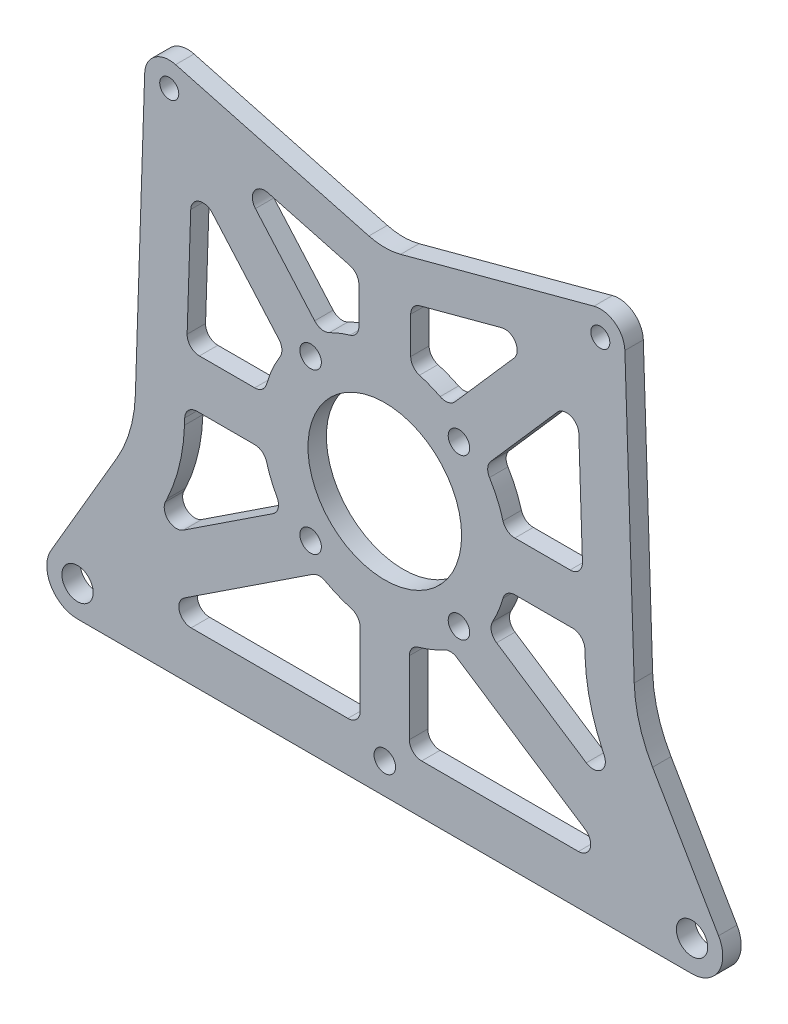
SolidWorks part; units mm, degrees
ref_plane "前视基准面" through (0, 0, 0) normal (0, 0, 1) x (1, 0, 0)
ref_plane "上视基准面" through (0, 0, 0) normal (0, 1, 0) x (1, 0, 0)
ref_plane "右视基准面" through (0, 0, 0) normal (1, 0, 0) x (0, 0, -1)
other "Configuration Table"
sketch "草图1" plane through (0, 0, 0) normal (0, 0, 1) x (1, 0, 0)
  line L0 (0, 0) -> (0, 112) construction
  line L1 (72.7192, 112) -> (-72.7192, 112) construction
  line L2 (-45, 15) -> (-95, 15) construction
  line L3 (-39.0719, 87.3817) -> (-40.5902, 41.2759)
  line L4 (-50, 5) -> (0, 5)
  line L5 (-54.3176, 12.5216) -> (-43.581, 30.9048)
  line L6 (-25, 5) -> (25, 5) construction
  line L7 (0, 5) -> (0, 96.5)
  line L8 (-34.0395, 91.1139) -> (0, 82)
  line L9 (-55, 10) -> (-55, 0)
  line L10 (-88.7574, 0) -> (88.7574, 0) construction
  line L11 (12.07, 35) -> (-12.07, 35) construction
  line L12 (12.07, 35) -> (12.07, 61) construction
  line L13 (12.07, 61) -> (-12.07, 61) construction
  line L14 (-12.07, 35) -> (-12.07, 61) construction
  line L15 (12.07, 35) -> (-12.07, 61) construction
  line L16 (12.07, 61) -> (-12.07, 35) construction
  line L17 (-55, 0) -> (0, 0)
  line L18 (0, 0) -> (0, 5)
  circle A0 centre (-35.074, 87.25) radius 1.55
  circle A4 centre (-50, 10) radius 2.55
  arc A5 (-45, 5) -> (-45, 15) centre (-45, 10) ccw construction
  circle A6 centre (-35.074, 87.25) radius 4
  circle A7 centre (-50, 10) radius 5
  circle A8 centre (-12.07, 61) radius 1.75
  circle A9 centre (12.07, 61) radius 1.75
  circle A10 centre (-12.07, 35) radius 1.75
  circle A11 centre (12.07, 35) radius 1.75
  arc A12 (-62.5783, 20) -> (-43.5752, 53.0852) centre (-62.5783, 42) ccw construction
  arc A13 (-62.5783, 20) -> (-40.5902, 41.2759) centre (-62.5783, 42) ccw
  point P32 (0, 48)
  dimension "D1" = 5
  dimension "D3" = 26
  dimension "D5" = 8
  dimension "D6" = 3.1
  dimension "D8" = 5.1
  dimension "D9" = 10
  dimension "D11" = 3.5
  dimension "D12" = 3.5
  dimension "D13" = 3.5
  dimension "D14" = 3.5
  dimension "D2" = 5
  dimension "D4" = 24.14
  dimension "D7" = 35
  dimension "D10" = 55
  dimension "D15" = 47
extrude "凸台-拉伸1" add sketch "草图1" along normal blind 3 contours A13 L5 A7 L4 L7 L8 A6 L3 A10 A8 | A6 A0 | A7 A4
mirror "镜向1" about plane through (0, 0, 3) normal (-1, 0, 0) of "凸台-拉伸1"
fillet "圆角1" radius 10 1 edges at (0, 82, 1.5)
sketch "草图2" plane through (0, 0, 3) normal (0, 0, 1) x (1, 0, 0)
  line L0 (25, 15) -> (-25, 15) construction
  circle A0 centre (0, 10) radius 1.75
  point P5 (0, 10)
  dimension "D1" = 5
  dimension "D3" = 3.5
  dimension "D2" = 10
extrude "切除-拉伸1" cut sketch "草图2" against normal blind 3
sketch "草图4" plane through (0, 0, 3) normal (0, 0, 1) x (1, 0, 0)
  line L0 (0, 61) -> (0, 35) construction
  line L1 (-12.07, 61) -> (12.07, 61)
  line L2 (-12.07, 61) -> (-12.07, 35)
  line L3 (-12.07, 35) -> (12.07, 35)
  line L4 (12.07, 61) -> (12.07, 35)
  line L5 (-12.07, 48) -> (12.07, 48) construction
  line L6 (12.07, 35) -> (50, 10) construction
  line L7 (35.074, 87.25) -> (12.07, 61) construction
  line L8 (-35.074, 87.25) -> (-12.07, 61) construction
  line L9 (-50, 10) -> (-12.07, 35) construction
  line L10 (0, 35) -> (0, 10) construction
  line L11 (0, 68) -> (0, 82.3522)
  line L12 (0, 28) -> (0, 10)
  line L13 (-32.5946, 41.0126) -> (-31.0762, 87.1183)
  line L14 (-39.0719, 87.3817) -> (-40.5902, 41.2759) construction
  line L15 (-39.0719, 87.3817) -> (-40.5902, 41.2759)
  line L16 (-31.4094, 76.9992) -> (-16.2336, 59.682)
  line L17 (-35.4302, 29.2337) -> (-45.4753, 7.8723)
  line L18 (-38.7284, 22.2199) -> (-16.5814, 36.8172)
  line L19 (-25.3928, 82.2718) -> (-10.217, 64.9546)
  line L20 (-25.3928, 82.2718) -> (-4.217, 76.6021)
  line L21 (-34.0395, 91.1139) -> (-2.5863, 82.6925) construction
  line L22 (-34.0395, 91.1139) -> (-2.5863, 82.6925)
  line L24 (-4.217, 76.6021) -> (-4.217, 67.5504)
  line L25 (-34.3258, 15.5403) -> (-12.1789, 30.1376)
  line L26 (-12.1789, 30.1376) -> (-10.7072, 31.1075)
  line L27 (-34.3258, 15.5403) -> (-38.18, 13)
  line L28 (-38.18, 13) -> (-4, 13)
  line L29 (-4, 13) -> (-4, 28.4041)
  circle A0 centre (0, 48) radius 12.5
  circle A1 centre (0, 48) radius 20
  circle A2 centre (-50, 10) radius 5
  circle A3 centre (-35.074, 87.25) radius 4
  circle A4 centre (35.074, 87.25) radius 4
  circle A5 centre (50, 10) radius 5
  circle A6 centre (0, 10) radius 5
  arc A7 (-2.5863, 82.6925) -> (2.5863, 82.6925) centre (0, 92.3522) ccw construction
  circle A8 centre (-62.5783, 42) radius 30
  circle A9 centre (0, 92.3522) radius 16.3049
  dimension "D3" = 25
  dimension "D4" = 40
  dimension "D5" = 8
  dimension "D6" = 10
  dimension "D7" = 10
  dimension "D8" = 8
  dimension "D9" = 10
  dimension "D10" = 8
  dimension "D12" = 4
  dimension "D13" = 4
  dimension "D1" = 26
  dimension "D2" = 24.14
  dimension "D11" = 4
extrude "切除-拉伸2" cut sketch "草图4" against normal blind 10 contours A1 L24 L20 L19 | A8 L17 L18 A1 L16 L13 | A1 L26 L25 L27 L28 L29
fillet "圆角2" radius 2 12 edges at (-4, 13, 1.5) (-38.18, 13, 1.5) (-10.7072, 31.1075, 1.5) (-4, 28.4041, 1.5) (-25.3928, 82.2718, 1.5) (-4.217, 76.6021, 1.5) (-4.217, 67.5504, 1.5) (-10.3542, 65.1111, 1.5) (-16.5814, 36.8172, 1.5) (-38.7284, 22.2199, 1.5) (-16.2336, 59.682, 1.5) (-31.4094, 76.9992, 1.5)
mirror "镜向2" about plane through (0, 0, 0) normal (1, 0, 0) of "圆角2", "切除-拉伸2"
sketch "草图5" plane through (0, 0, 3) normal (0, 0, 1) x (1, 0, 0)
  circle A0 centre (0, 48) radius 12.5
extrude "切除-拉伸3" cut sketch "草图5" against normal blind 10
sketch "草图6" plane through (0, 0, 3) normal (0, 0, 1) x (1, 0, 0)
  line L0 (-12.5, 48) -> (40.3688, 48)
  line L1 (39.0719, 87.3817) -> (40.5902, 41.2759) construction
  line L2 (-12.5, 48) -> (-32.3644, 48)
  line L4 (-32.2327, 52) -> (-19.5959, 52)
  line L5 (-32.5946, 41.0126) -> (-31.5761, 71.9397) construction
  line L6 (-32.4962, 44) -> (-19.5959, 44)
  line L7 (-32.4962, 44) -> (-32.2327, 52)
  circle A0 centre (0, 48) radius 12.5 construction
  arc A1 (-17.0419, 58.4677) -> (-17.5383, 38.3871) centre (0, 48) ccw construction
  arc A2 (-19.5959, 52) -> (-19.5959, 44) centre (0, 48) ccw
  dimension "D1" = 4
  dimension "D2" = 4
extrude "凸台-拉伸2" add sketch "草图6" against normal blind 3 contours A2 L4 L7 L2 | A2 L2 L7 L6
mirror "镜向3" about plane through (0, 0, 0) normal (1, 0, 0) of "凸台-拉伸2"
fillet "圆角3" radius 2 4 edges at (-19.5959, 44, 1.5) (-32.4962, 44, 1.5) (-19.5959, 52, 1.5) (-32.2327, 52, 1.5)
fillet "圆角4" radius 2 4 edges at (19.5959, 44, 1.5) (32.2327, 52, 1.5) (32.4962, 44, 1.5) (19.5959, 52, 1.5)
